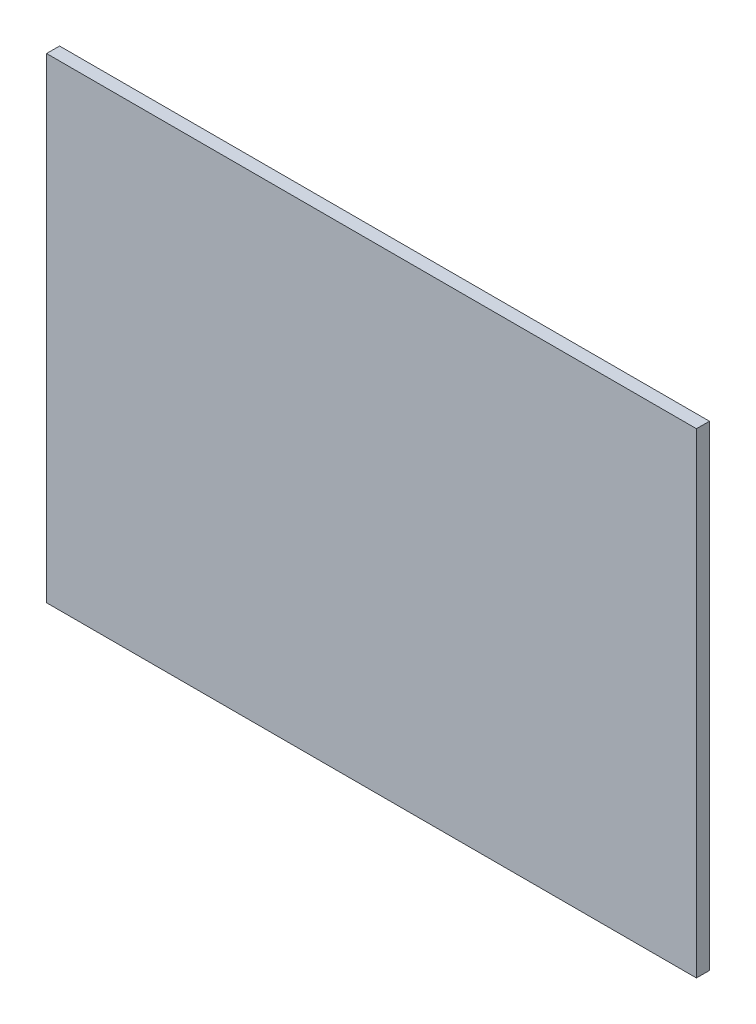
SolidWorks part; units mm, degrees
ref_plane "Front Plane" through (0, 0, 0) normal (0, 0, 1) x (1, 0, 0)
ref_plane "Top Plane" through (0, 0, 0) normal (0, 1, 0) x (1, 0, 0)
ref_plane "Right Plane" through (0, 0, 0) normal (1, 0, 0) x (0, 0, -1)
sketch "Sketch1" plane through (0, 0, 0) normal (0, 0, 1) x (1, 0, 0)
  line L1 (2500, 1830) -> (-2500, 1830)
  line L2 (2500, 1830) -> (2500, -1830)
  line L3 (2500, -1830) -> (-2500, -1830)
  line L4 (-2500, 1830) -> (-2500, -1830)
  line L5 (2500, 1830) -> (-2500, -1830) construction
  line L6 (2500, -1830) -> (-2500, 1830) construction
  point P0 (0, 0)
  dimension "D1" = 3660
  dimension "D2" = 5000
extrude "Boss-Extrude1" add sketch "Sketch1" along normal blind 100 contours L1 L4 L3 L2
